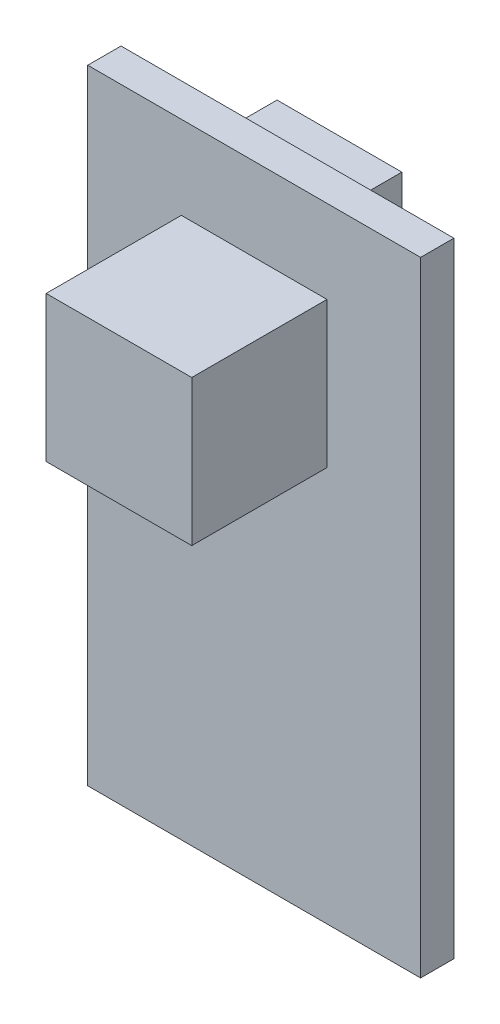
SolidWorks part; units mm, degrees
ref_plane "Front Plane" through (0, 0, 0) normal (0, 0, 1) x (1, 0, 0)
ref_plane "Top Plane" through (0, 0, 0) normal (0, 1, 0) x (1, 0, 0)
ref_plane "Right Plane" through (0, 0, 0) normal (1, 0, 0) x (0, 0, -1)
ref_plane "Plane1" through (0, 0, 13.1) normal (0, 0, 1) x (1, 0, 0)
sketch "Sketch1" plane through (0, 0, 13.1) normal (0, 0, 1) x (1, 0, 0)
  line L1 (14, -12) -> (30, -12)
  line L2 (14, -12) -> (14, 18)
  line L3 (14, 18) -> (30, 18)
  line L4 (30, -12) -> (30, 18)
  line L5 (14, -12) -> (30, 18) construction
  line L6 (14, 18) -> (30, -12) construction
  point P0 (22, 3)
extrude "Boss-Extrude1" add sketch "Sketch1" along normal blind 1.6
ref_plane "Plane2" through (0, 0, 10.6) normal (0, 0, 1) x (1, 0, 0)
sketch "Sketch2" plane through (0, 0, 10.6) normal (0, 0, 1) x (1, 0, 0)
  line L1 (19, -11) -> (25, -11)
  line L2 (19, -11) -> (19, 17)
  line L3 (19, 17) -> (25, 17)
  line L4 (25, -11) -> (25, 17)
  line L5 (19, -11) -> (25, 17) construction
  line L6 (19, 17) -> (25, -11) construction
  point P0 (22, 3)
extrude "Boss-Extrude2" add sketch "Sketch2" along normal blind 2.5
ref_plane "Plane3" through (0, 0, 14.7) normal (0, 0, 1) x (1, 0, 0)
sketch "Sketch3" plane through (0, 0, 14.7) normal (0, 0, 1) x (1, 0, 0)
  line L1 (18.5, 7) -> (25.5, 7)
  line L2 (18.5, 7) -> (18.5, 14)
  line L3 (18.5, 14) -> (25.5, 14)
  line L4 (25.5, 7) -> (25.5, 14)
  line L5 (18.5, 7) -> (25.5, 14) construction
  line L6 (18.5, 14) -> (25.5, 7) construction
  point P0 (22, 10.5)
extrude "Boss-Extrude3" add sketch "Sketch3" along normal blind 6.5
